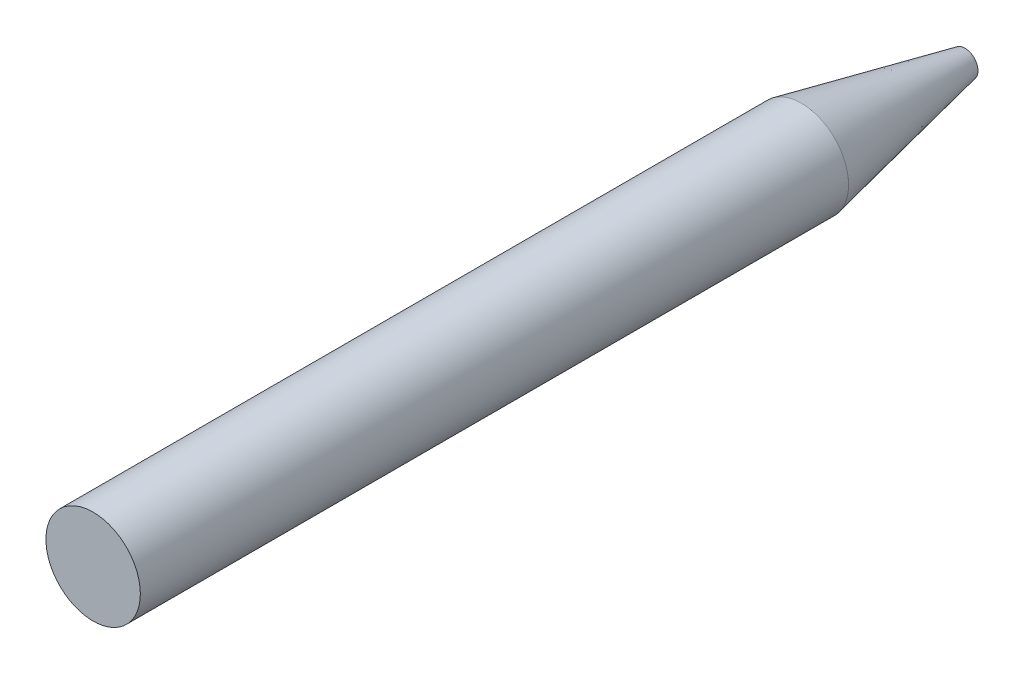
SolidWorks part; units mm, degrees
material "2014 Alloy"
ref_plane "Front Plane" through (0, 0, 0) normal (0, 0, 1) x (1, 0, 0)
ref_plane "Top Plane" through (0, 0, 0) normal (0, 1, 0) x (1, 0, 0)
ref_plane "Right Plane" through (0, 0, 0) normal (1, 0, 0) x (0, 0, -1)
sketch "Sketch1" plane through (0, 0, 0) normal (0, 0, 1) x (1, 0, 0)
  circle A0 centre (0, 0) radius 25.4
extrude "Boss-Extrude3" add sketch "Sketch1" along normal blind 381
sketch "Sketch2" plane through (0, 0, 0) normal (0, 1, 0) x (1, 0, 0)
  line L0 (-25.4, 0) -> (0, 0)
  line L1 (0, 0) -> (0, 88.0112)
  line L2 (0, 88.0112) -> (-7.011, 88.0112)
  line L3 (-7.011, 88.0112) -> (-25.4, 0)
revolve "Revolve1" add sketch "Sketch2" angle 360 about L1
